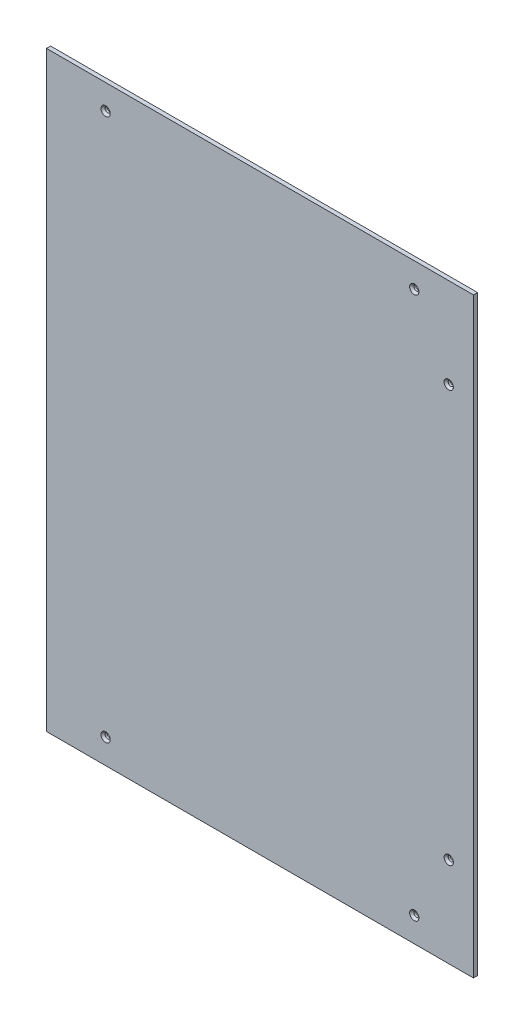
SolidWorks part; units mm, degrees
material "1.4301 (X5CrNi18-10)"
ref_plane "Plan de face" through (0, 0, 0) normal (0, 0, 1) x (1, 0, 0)
ref_plane "Plan de dessus" through (0, 0, 0) normal (0, 1, 0) x (1, 0, 0)
ref_plane "Plan de droite" through (0, 0, 0) normal (1, 0, 0) x (0, 0, -1)
sketch "Esquisse1" plane through (0, 0, 0) normal (0, 0, 1) x (1, 0, 0)
  line L1 (-207.5, -287.5) -> (207.5, -287.5)
  line L2 (-207.5, -287.5) -> (-207.5, 287.5)
  line L3 (-207.5, 287.5) -> (207.5, 287.5)
  line L4 (207.5, -287.5) -> (207.5, 287.5)
  line L5 (-207.5, -287.5) -> (207.5, 287.5) construction
  line L6 (-207.5, 287.5) -> (207.5, -287.5) construction
  point P0 (0, 0)
  dimension "D1" = 575
  dimension "D2" = 415
extrude "Boss.-Extru.1" add sketch "Esquisse1" along normal mid plane 4
sketch "Esquisse2" plane through (0, 0, 2) normal (0, 0, 1) x (1, 0, 0)
  line L0 (-207.5, 287.5) -> (-207.5, -287.5) construction
  line L1 (183.5, -263.5) -> (-183.5, -263.5) construction
  line L2 (183.5, -263.5) -> (183.5, 263.5) construction
  line L3 (183.5, 263.5) -> (-183.5, 263.5) construction
  line L4 (-183.5, -263.5) -> (-183.5, 263.5) construction
  line L5 (183.5, -263.5) -> (-183.5, 263.5) construction
  line L6 (183.5, 263.5) -> (-183.5, -263.5) construction
  line L7 (-207.5, -287.5) -> (207.5, -287.5) construction
  line L8 (-183.5, 0) -> (183.5, 0) construction
  line L9 (0, -263.5) -> (0, 263.5) construction
  circle A0 centre (-150, -263.5) radius 2.5
  circle A1 centre (150, -263.5) radius 2.5
  circle A2 centre (183.5, -200) radius 2.5
  circle A3 centre (183.5, 200) radius 2.5
  circle A4 centre (-150, 263.5) radius 2.5
  circle A5 centre (150, 263.5) radius 2.5
  point P0 (0, 0)
  dimension "D4" = 400
  dimension "D5" = 5
  dimension "D1" = 24
  dimension "D2" = 24
  dimension "D3" = 300
extrude "Enlèv. mat.-Extru.1" cut sketch "Esquisse2" against normal through all
chamfer "Chanfrein1" distance 2 angle 45 6 edges at (152.5, 263.5, 2) (-147.5, 263.5, 2) (186, 200, 2) (186, -200, 2) (152.5, -263.5, 2) (-147.5, -263.5, 2)
